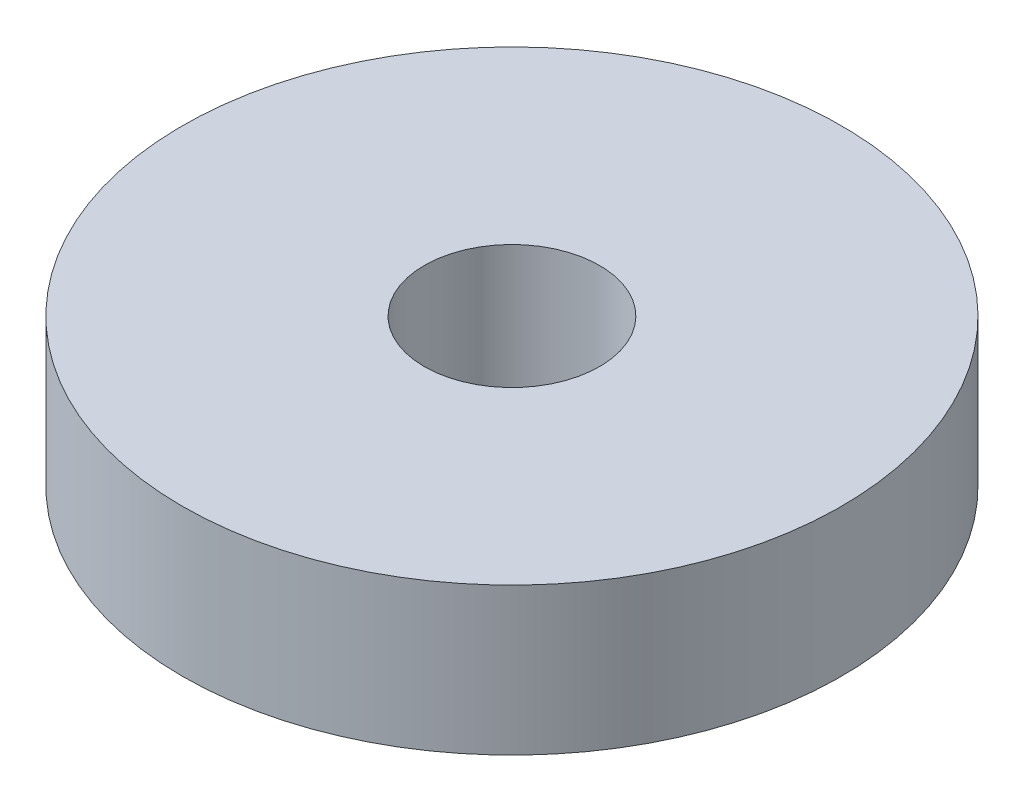
SolidWorks part; units mm, degrees
ref_plane "Front Plane" through (0, 0, 0) normal (0, 0, 1) x (1, 0, 0)
ref_plane "Top Plane" through (0, 0, 0) normal (0, 1, 0) x (1, 0, 0)
ref_plane "Right Plane" through (0, 0, 0) normal (1, 0, 0) x (0, 0, -1)
sketch "Sketch1" plane through (0, 0, 0) normal (0, 1, 0) x (1, 0, 0)
  circle A0 centre (0, 0) radius 2.5
  circle A1 centre (0, 0) radius 9.4
  dimension "D1" = 5
  dimension "D2" = 18.8
extrude "Boss-Extrude1" add sketch "Sketch1" along normal blind 4.2
